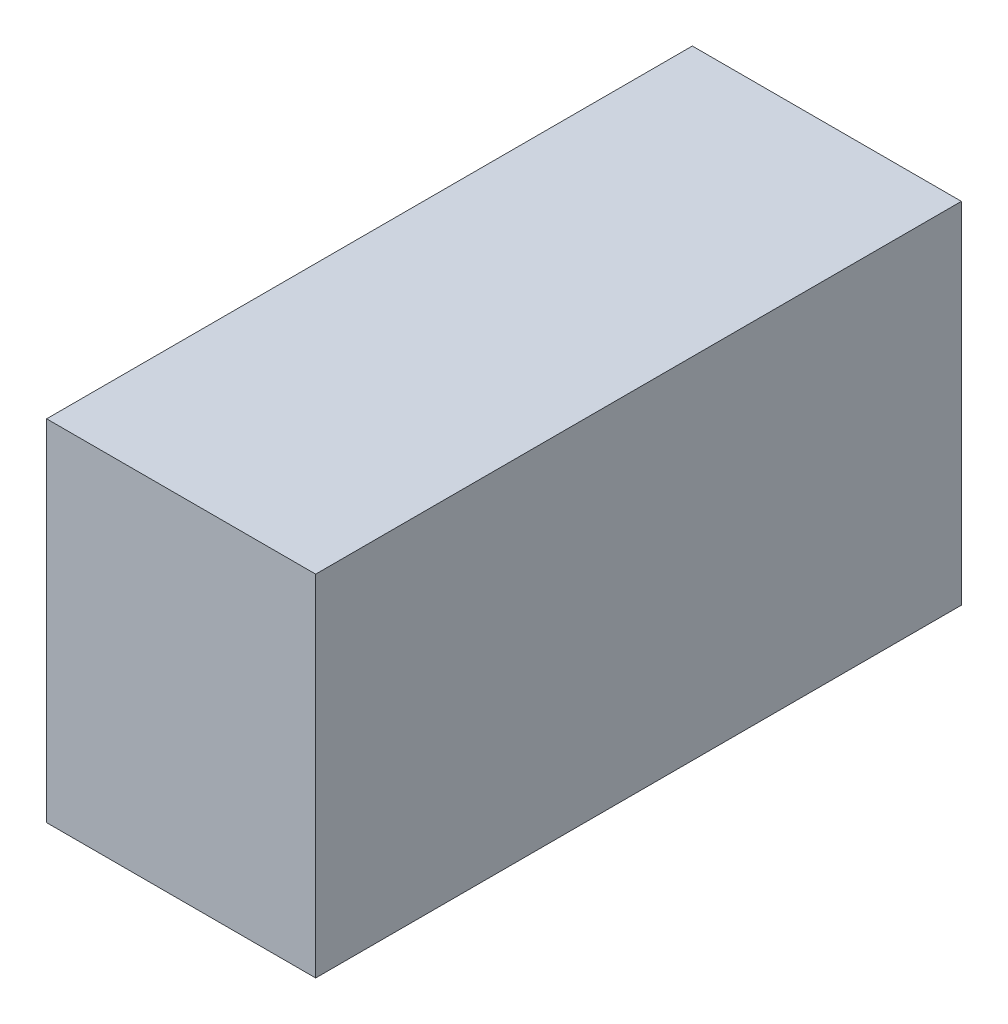
SolidWorks part; units mm, degrees
ref_plane "Front Plane" through (0, 0, 0) normal (0, 0, 1) x (1, 0, 0)
ref_plane "Top Plane" through (0, 0, 0) normal (0, 1, 0) x (1, 0, 0)
ref_plane "Right Plane" through (0, 0, 0) normal (1, 0, 0) x (0, 0, -1)
sketch "Sketch1" plane through (0, 0, 0) normal (0, 1, 0) x (1, 0, 0)
  line L1 (0, 0) -> (-12.7, 0)
  line L2 (0, 0) -> (0, 25.4)
  line L3 (0, 25.4) -> (-12.7, 25.4)
  line L4 (-12.7, 0) -> (-12.7, 25.4)
  dimension "D1" = 12.7
  dimension "D2" = 25.4
extrude "Boss-Extrude1" add sketch "Sketch1" along normal blind 16.51
sketch "Sketch2" plane through (0, 0, 0) normal (0, 0, 1) x (1, 0, 0)
  line L1 (0, 16.51) -> (-12.7, 16.51)
  line L2 (0, 16.51) -> (0, 0)
  line L3 (0, 0) -> (-12.7, 0)
  line L4 (-12.7, 16.51) -> (-12.7, 0)
extrude "Boss-Extrude2" add sketch "Sketch2" along normal blind 6.35
sketch "Sketch6" plane through (0, 0, 6.35) normal (0, 0, 1) x (1, 0, 0)
  line L0 (0, 16.51) -> (-12.7, 16.51) construction
  line L1 (-12.7, 0) -> (-6.35, 0)
  line L2 (-12.7, 0) -> (-12.7, 16.51)
  line L3 (-12.7, 16.51) -> (-6.35, 16.51)
  line L4 (-6.35, 0) -> (-6.35, 16.51)
sketch "Sketch10" plane through (0, 16.51, 0) normal (0, 1, 0) x (1, 0, 0)
  line L0 (-13.3122, 24.13) -> (0.5407, 24.13)
  line L1 (-14.3933, 24.13) -> (-10.3717, 24.13) construction
extrude "Cut-Extrude2" cut sketch "Sketch10" against normal through all both and the other way through all contours L0
sketch "Sketch12" plane through (0, 16.51, 0) normal (0, 1, 0) x (1, 0, 0)
  line L0 (-6.35, 24.13) -> (-6.35, -6.35) construction
  line L1 (0, 24.13) -> (-12.7, 24.13) construction
equation "\"Foamcore\" = .1875in"
equation "\"Mdf\" = .25in"
equation "\"Gmaterial\"= \"Mdf\""
equation "\"D1@Sketch1\"=\"Gmaterial\"*2"
equation "\"D1@Boss-Extrude1\"=\"Gmaterial\"+0.4"
equation "\"D1@Boss-Extrude2\"=\"Gmaterial\""
